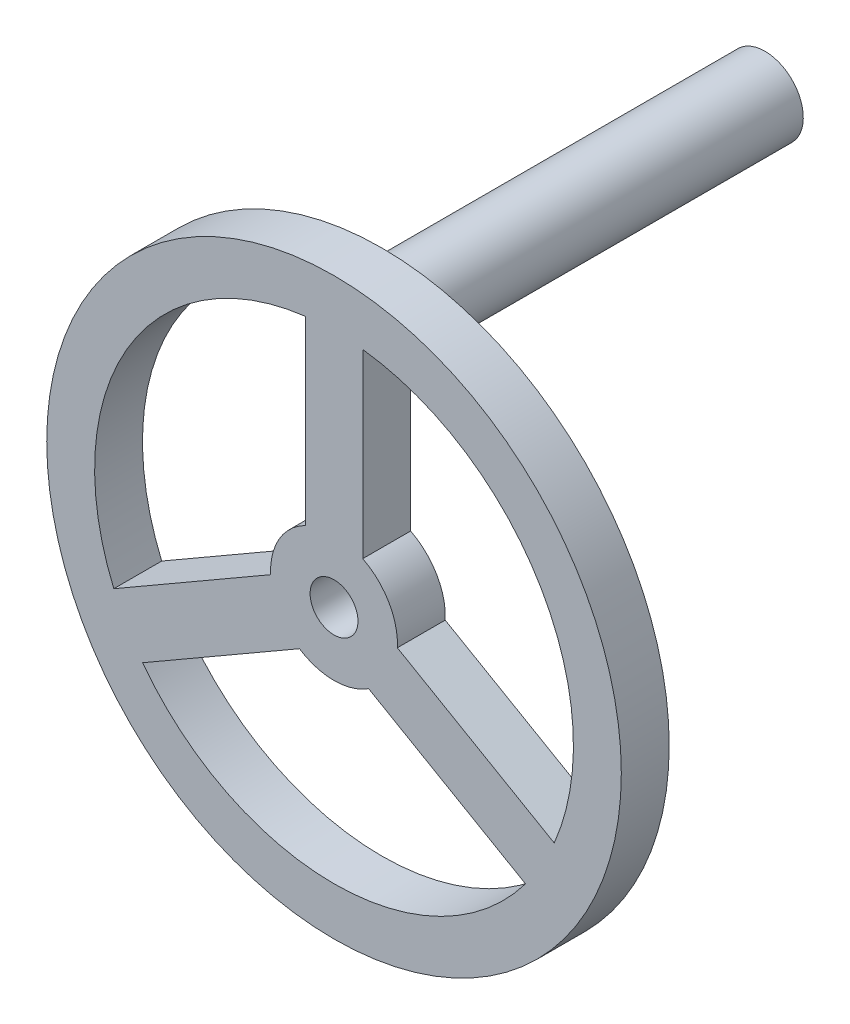
SolidWorks part; units mm, degrees
ref_plane "Front Plane" through (0, 0, 0) normal (0, 0, 1) x (1, 0, 0)
ref_plane "Top Plane" through (0, 0, 0) normal (0, 1, 0) x (1, 0, 0)
ref_plane "Right Plane" through (0, 0, 0) normal (1, 0, 0) x (0, 0, -1)
sketch "Sketch1" plane through (0, 0, 0) normal (0, 0, 1) x (1, 0, 0)
  line L5 (0, 16.8161) -> (0, 63.5) construction
  line L6 (-7.62, 63.0411) -> (-7.62, 14.9906)
  line L14 (7.62, 63.0411) -> (7.62, 14.9906)
  line L15 (58.4052, -24.9215) -> (16.7922, -0.8962)
  line L16 (50.7852, -38.1197) -> (9.1722, -14.0944)
  line L17 (-50.7852, -38.1197) -> (-9.1722, -14.0944)
  line L18 (-58.4052, -24.9215) -> (-16.7922, -0.8962)
  circle A0 centre (0, 0) radius 76.2
  circle A1 centre (0, 0) radius 63.5
  circle A2 centre (0, 0) radius 16.8161
  circle A3 centre (0, 0) radius 6.35
  point P22 (0, 0)
  point P23 (0, 0)
  dimension "D1" = 152.4
  dimension "D2" = 12.7
  dimension "D5" = 12.7
  dimension "D3" = 7.62
  dimension "D4" = 7.62
  dimension "D6" = 3
extrude "Boss-Extrude1" add sketch "Sketch1" along normal blind 12.7 contours A0 A1 | A2 L5 A1 L6 | L5 A2 L14 A1 | A2 L18 A1 L17 | A2 L16 A1 L15 | A2 A3
sketch "Sketch2" plane through (0, 0, 0) normal (0, 0, -1) x (-1, 0, 0)
  circle A0 centre (0, 60.4278) radius 10.16
  point P2 (0, 60.4278)
  dimension "D1" = 20.32
extrude "Boss-Extrude2" add sketch "Sketch2" along normal blind 101.6
